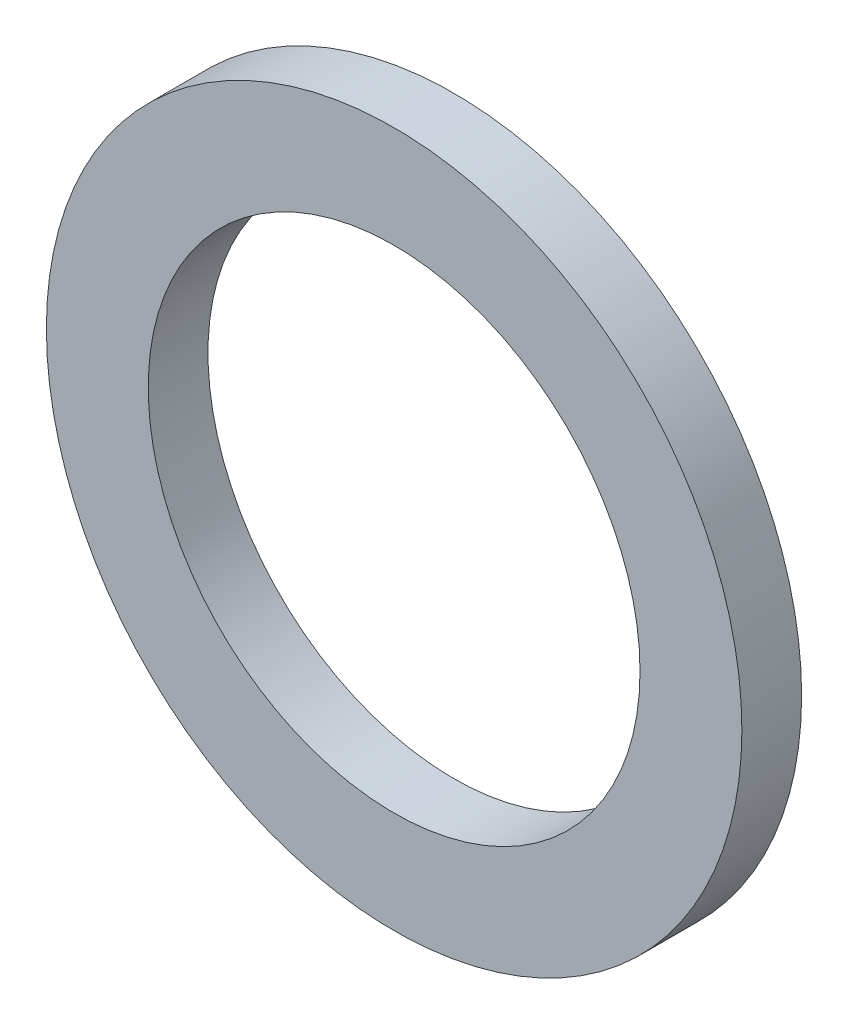
SolidWorks part; units mm, degrees
ref_plane "Plan1" through (0, 0, 0) normal (0, 0, 1) x (1, 0, 0)
ref_plane "Plan2" through (0, 0, 0) normal (0, 1, 0) x (1, 0, 0)
ref_plane "Plan3" through (0, 0, 0) normal (1, 0, 0) x (0, 0, -1)
sketch "Esquisse1" plane through (0, 0, 0) normal (0, 0, 1) x (1, 0, 0)
  circle A0 centre (0, 0) radius 7
  circle A1 centre (0, 0) radius 9.9
  dimension "D1" = 14
  dimension "D2" = 19.8
extrude "Base-Extrusion" add sketch "Esquisse1" along normal blind 1.7
